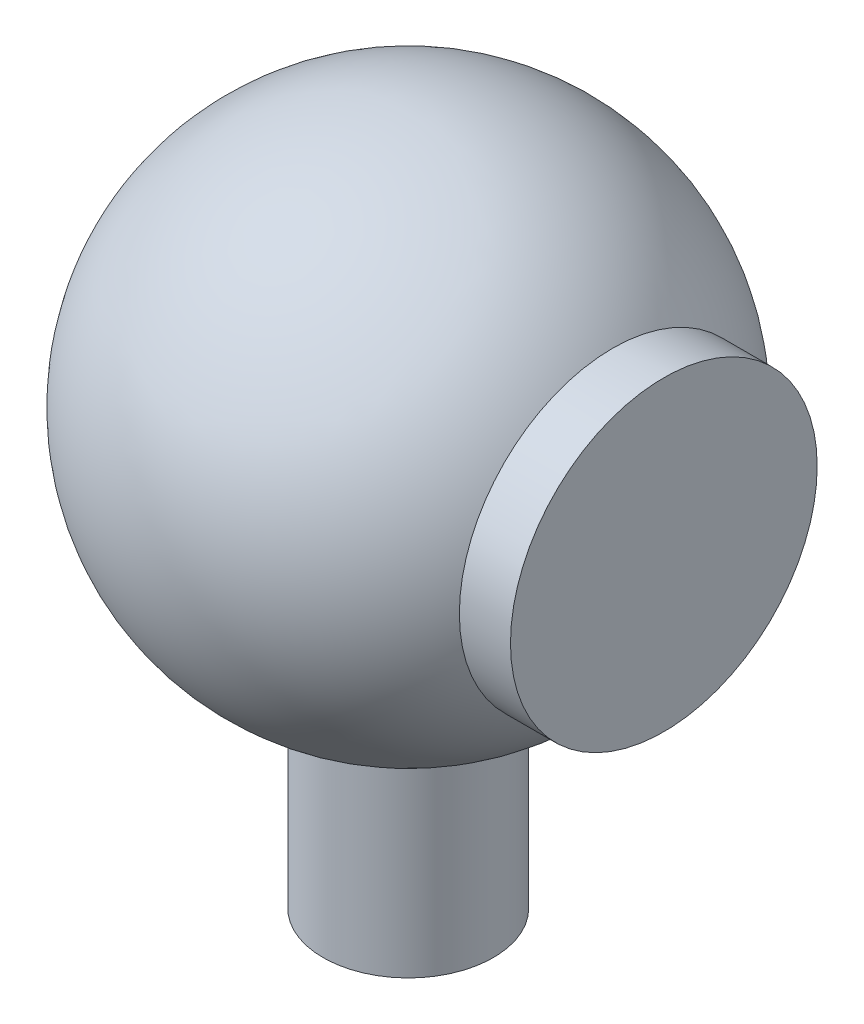
SolidWorks part; units mm, degrees
material "Hexcel AS4C (3000 волосков)"
ref_plane "Спереди" through (0, 0, 0) normal (0, 0, 1) x (1, 0, 0)
ref_plane "Сверху" through (0, 0, 0) normal (0, 1, 0) x (1, 0, 0)
ref_plane "Справа" through (0, 0, 0) normal (1, 0, 0) x (0, 0, -1)
sketch "Эскиз1" plane through (0, 0, 0) normal (0, 0, 1) x (1, 0, 0)
  line L0 (0, 0) -> (22.5, 0) construction
  line L1 (22.5, -13.5) -> (22.5, 0)
  line L2 (-18, -13.5) -> (18, -13.5) construction
  line L3 (-18, -13.5) -> (-18, 13.5) construction
  line L4 (-18, 13.5) -> (18, 13.5) construction
  line L5 (18, -13.5) -> (18, 13.5) construction
  line L6 (-18, -13.5) -> (18, 13.5) construction
  line L7 (-18, 13.5) -> (18, -13.5) construction
  line L8 (22.5, 0) -> (-22.5, 0)
  line L9 (22.5, -13.5) -> (18, -13.5)
  line L10 (0, 0) -> (50000, 0) construction
  circle A0 centre (0, 0) radius 22.5 construction
  arc A1 (-22.5, 0) -> (18, -13.5) centre (0, 0) ccw
  dimension "D1" = 45
  dimension "D2" = 27
revolve "Повернуть5" add sketch "Эскиз1" angle 360 about L10
sketch "Эскиз2" plane through (0, 0, 0) normal (0, 0, 1) x (1, 0, 0)
  line L0 (0, 0) -> (0, -22.5) construction
  line L2 (-7.5, 21.2132) -> (7.5, 21.2132) construction
  line L3 (-7.5, 21.2132) -> (-7.5, -21.2132) construction
  line L4 (-7.5, -21.2132) -> (7.5, -21.2132) construction
  line L5 (7.5, 21.2132) -> (7.5, -21.2132) construction
  line L6 (-7.5, 21.2132) -> (7.5, -21.2132) construction
  line L7 (-7.5, -21.2132) -> (7.5, 21.2132) construction
  line L8 (0, -21.2132) -> (7.5, -21.2132)
  line L9 (0, -21.2132) -> (0, -38.2132)
  line L10 (0, -38.2132) -> (7.5, -38.2132)
  line L11 (7.5, -21.2132) -> (7.5, -38.2132)
  arc A0 (18, 13.5) -> (18, -13.5) centre (0, 0) ccw construction
  dimension "D1" = 15
  dimension "D2" = 17
revolve "Повернуть6" add sketch "Эскиз2" angle 360 about L9
